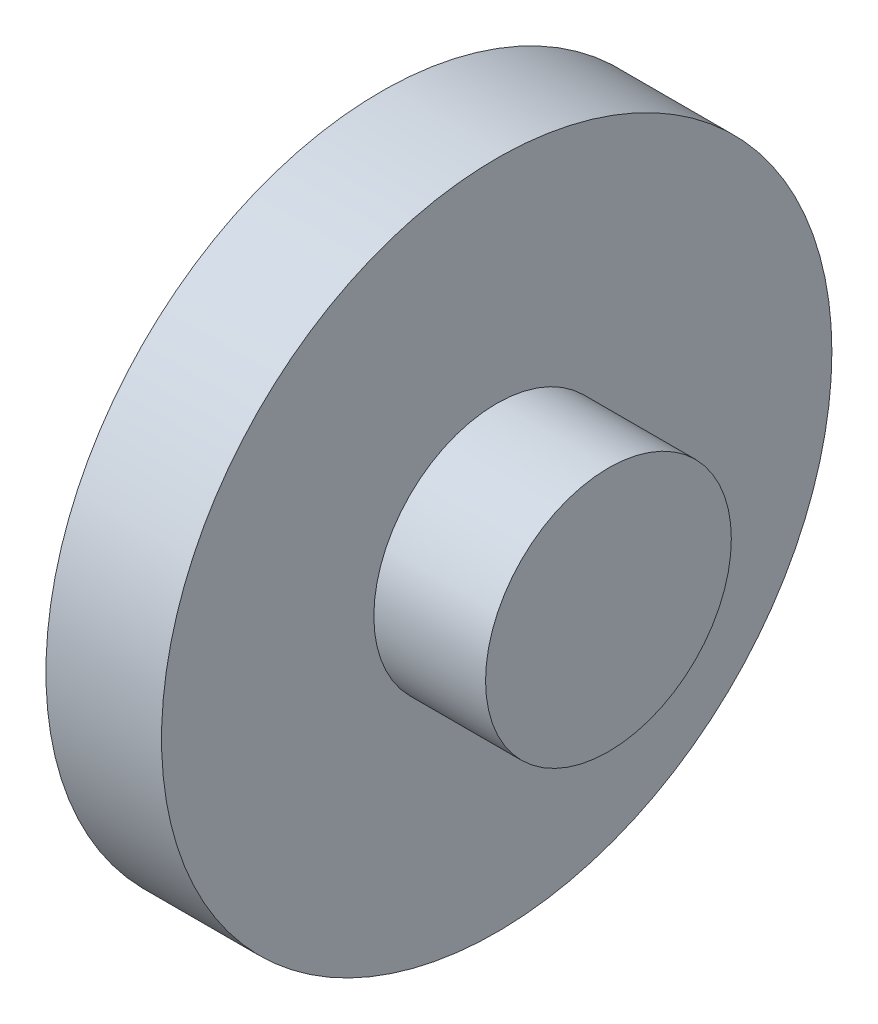
SolidWorks part; units mm, degrees
ref_plane "Front Plane" through (0, 0, 0) normal (0, 0, 1) x (1, 0, 0)
ref_plane "Top Plane" through (0, 0, 0) normal (0, 1, 0) x (1, 0, 0)
ref_plane "Right Plane" through (0, 0, 0) normal (1, 0, 0) x (0, 0, -1)
sketch "Sketch1" plane through (0, 0, 0) normal (1, 0, 0) x (0, 0, -1)
  line L0 (-15, 0) -> (15, 0) construction
  line L1 (-1.5875, 8.35) -> (1.5875, 8.35)
  line L2 (-1.5875, 8.35) -> (-1.5875, -8.35)
  line L3 (-1.5875, -8.35) -> (1.5875, -8.35)
  line L4 (1.5875, 8.35) -> (1.5875, -8.35)
  line L5 (0, -15) -> (0, 15) construction
  circle A0 centre (0, 0) radius 15
  dimension "D1" = 30
  dimension "D2" = 3.175
  dimension "D3" = 16.7
extrude "Boss-Extrude1" add sketch "Sketch1" along normal blind 4.175
sketch "Sketch2" plane through (4.175, 0, 0) normal (1, 0, 0) x (0, 0, -1)
  circle A0 centre (0, 0) radius 15 construction
  circle A1 centre (0, 0) radius 15
extrude "Boss-Extrude2" add sketch "Sketch2" along normal blind 1
sketch "Sketch3" plane through (5.175, 0, 0) normal (1, 0, 0) x (0, 0, -1)
  circle A0 centre (0, 0) radius 5.5
  dimension "D1" = 11
extrude "Boss-Extrude3" add sketch "Sketch3" along normal blind 5
